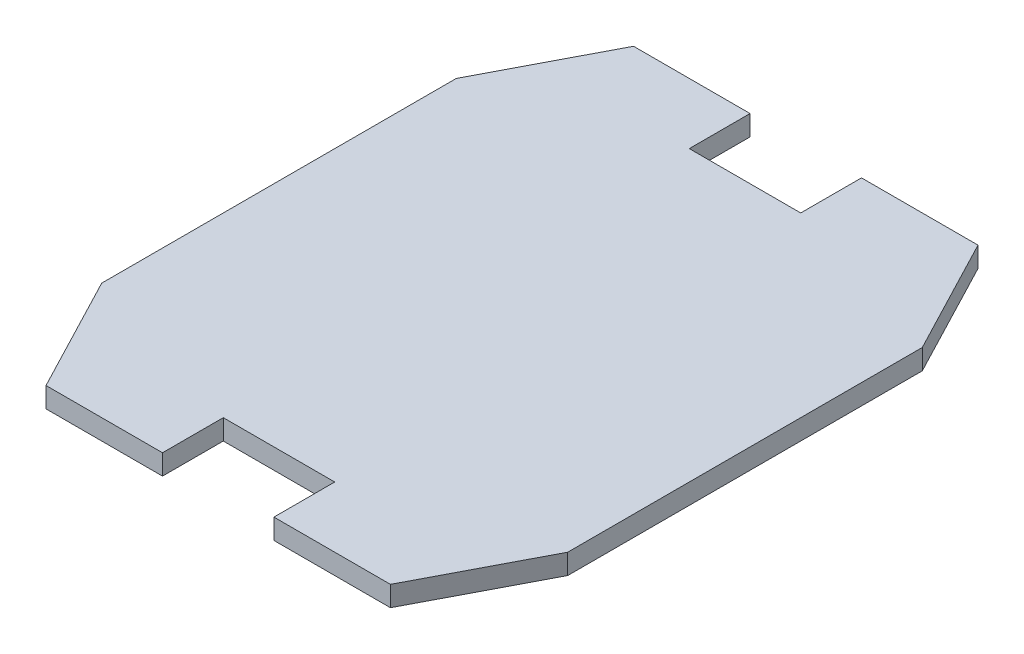
SolidWorks part; units mm, degrees
ref_plane "Front Plane" through (0, 0, 0) normal (0, 0, 1) x (1, 0, 0)
ref_plane "Top Plane" through (0, 0, 0) normal (0, 1, 0) x (1, 0, 0)
ref_plane "Right Plane" through (0, 0, 0) normal (1, 0, 0) x (0, 0, -1)
sketch "Sketch1" plane through (0, 0, 0) normal (0, 1, 0) x (1, 0, 0)
  line L1 (-155, 145) -> (155, 145)
  line L2 (-155, 145) -> (-155, -145)
  line L3 (-155, -145) -> (155, -145)
  line L4 (155, 145) -> (155, -145)
  line L5 (-155, 145) -> (155, -145) construction
  line L6 (-155, -145) -> (155, 145) construction
  point P0 (0, 0)
  dimension "D1" = 310
  dimension "D2" = 290
extrude "Boss-Extrude1" add sketch "Sketch1" along normal blind 10
sketch "Sketch2" plane through (0, 10, 0) normal (0, 1, 0) x (1, 0, 0)
  line L0 (-85, 145) -> (-115, 87.5)
  line L1 (155, 145) -> (-155, 145) construction
  line L2 (-115, 87.5) -> (-115, -87.5)
  line L5 (-115, -87.5) -> (-85, -145)
  line L6 (-155, -145) -> (155, -145) construction
  line L7 (-85, -145) -> (-155, -145)
  line L8 (-155, -145) -> (-155, 145)
  line L9 (-155, 145) -> (-85, 145)
  line L10 (0, -39.53) -> (0, 39.53) construction
  line L11 (155, -145) -> (155, 145)
  line L12 (85, -145) -> (155, -145)
  line L13 (115, -87.5) -> (85, -145)
  line L14 (115, 87.5) -> (115, -87.5)
  line L15 (85, 145) -> (115, 87.5)
  line L16 (155, 145) -> (85, 145)
  dimension "D1" = 70
  dimension "D2" = 175
  dimension "D3" = 40
extrude "Cut-Extrude1" cut sketch "Sketch2" against normal through all
sketch "Sketch3" plane through (0, 10, 0) normal (0, 1, 0) x (1, 0, 0)
  line L0 (85, 145) -> (-85, 145) construction
  line L1 (27.5, 145) -> (-27.5, 145)
  line L2 (27.5, 145) -> (27.5, 115)
  line L3 (27.5, 115) -> (-27.5, 115)
  line L4 (-27.5, 145) -> (-27.5, 115)
  line L5 (-204.015, 0) -> (204.015, 0) construction
  line L6 (-27.5, -145) -> (-27.5, -115)
  line L7 (27.5, -145) -> (-27.5, -145)
  line L8 (27.5, -145) -> (27.5, -115)
  line L9 (27.5, -115) -> (-27.5, -115)
  dimension "D1" = 55
  dimension "D2" = 30
  dimension "D3" = 27.5
extrude "Cut-Extrude2" cut sketch "Sketch3" against normal through all
